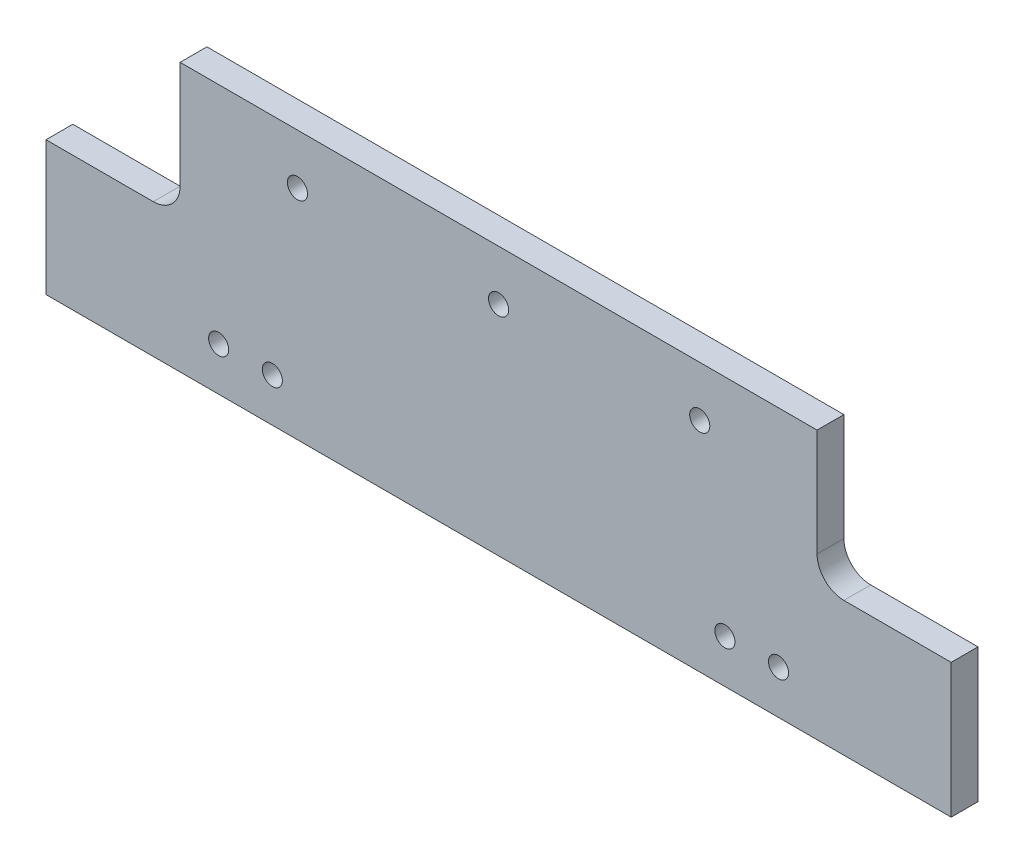
SolidWorks part; units mm, degrees
material "A-玻璃纤维"
ref_plane "前视基准面" through (0, 0, 0) normal (0, 0, 1) x (1, 0, 0)
ref_plane "上视基准面" through (0, 0, 0) normal (0, 1, 0) x (1, 0, 0)
ref_plane "右视基准面" through (0, 0, 0) normal (1, 0, 0) x (0, 0, -1)
sketch "草图1" plane through (0, 0, 0) normal (0, 0, 1) x (1, 0, 0)
  line L1 (-67.5, 20) -> (67.5, 20)
  line L2 (-67.5, 20) -> (-67.5, -20)
  line L3 (-67.5, -20) -> (67.5, -20)
  line L4 (67.5, 20) -> (67.5, -20)
  line L5 (-67.5, 20) -> (67.5, -20) construction
  line L6 (-67.5, -20) -> (67.5, 20) construction
  point P0 (0, 0)
  dimension "D1" = 135
  dimension "D2" = 40
extrude "凸台-拉伸1" add sketch "草图1" along normal blind 4
sketch "草图2" plane through (0, 0, 4) normal (0, 0, 1) x (1, 0, 0)
  line L0 (0, 20) -> (0, -20) construction
  line L1 (-67.5, 20) -> (-47.5, 20)
  line L2 (-67.5, 20) -> (-67.5, 0)
  line L3 (-67.5, 0) -> (-47.5, 0)
  line L4 (-47.5, 20) -> (-47.5, 0)
  line L5 (67.5, 20) -> (-67.5, 20) construction
  line L6 (-67.5, -20) -> (67.5, -20) construction
  line L7 (47.5, 20) -> (47.5, 0)
  line L8 (67.5, 0) -> (47.5, 0)
  line L9 (67.5, 20) -> (67.5, 0)
  line L10 (67.5, 20) -> (47.5, 20)
  dimension "D1" = 20
  dimension "D2" = 20
extrude "切除-拉伸1" cut sketch "草图2" against normal through all
fillet "圆角1" radius 4 2 edges at (47.5, 0, 2) (-47.5, 0, 2)
sketch "草图3" plane through (0, 0, 4) normal (0, 0, 1) x (1, 0, 0)
  line L0 (0, 20) -> (0, -20) construction
  line L1 (47.5, 20) -> (-47.5, 20) construction
  line L2 (-67.5, -20) -> (67.5, -20) construction
  circle A0 centre (0, 12.5) radius 1.5
  circle A1 centre (-30, 12.5) radius 1.5
  circle A2 centre (30, 12.5) radius 1.5
  dimension "D1" = 30
  dimension "D2" = 3
  dimension "D3" = 7.5
extrude "切除-拉伸2" cut sketch "草图3" against normal through all
sketch "草图4" plane through (0, 0, 4) normal (0, 0, 1) x (1, 0, 0)
  line L0 (-67.5, -13.5) -> (67.5, -13.5) construction
  line L1 (-67.5, 0) -> (-67.5, -20) construction
  line L2 (67.5, -20) -> (67.5, 0) construction
  line L3 (-67.5, -20) -> (67.5, -20) construction
  line L4 (0, -13.5) -> (0, -20) construction
  circle A0 centre (-41.75, -13.5) radius 1.5
  circle A1 centre (-33.75, -13.5) radius 1.5
  circle A2 centre (33.75, -13.5) radius 1.5
  circle A3 centre (41.75, -13.5) radius 1.5
  dimension "D2" = 8
  dimension "D3" = 3
  dimension "D1" = 6.5
  dimension "D4" = 75.5
extrude "切除-拉伸3" cut sketch "草图4" against normal through all
